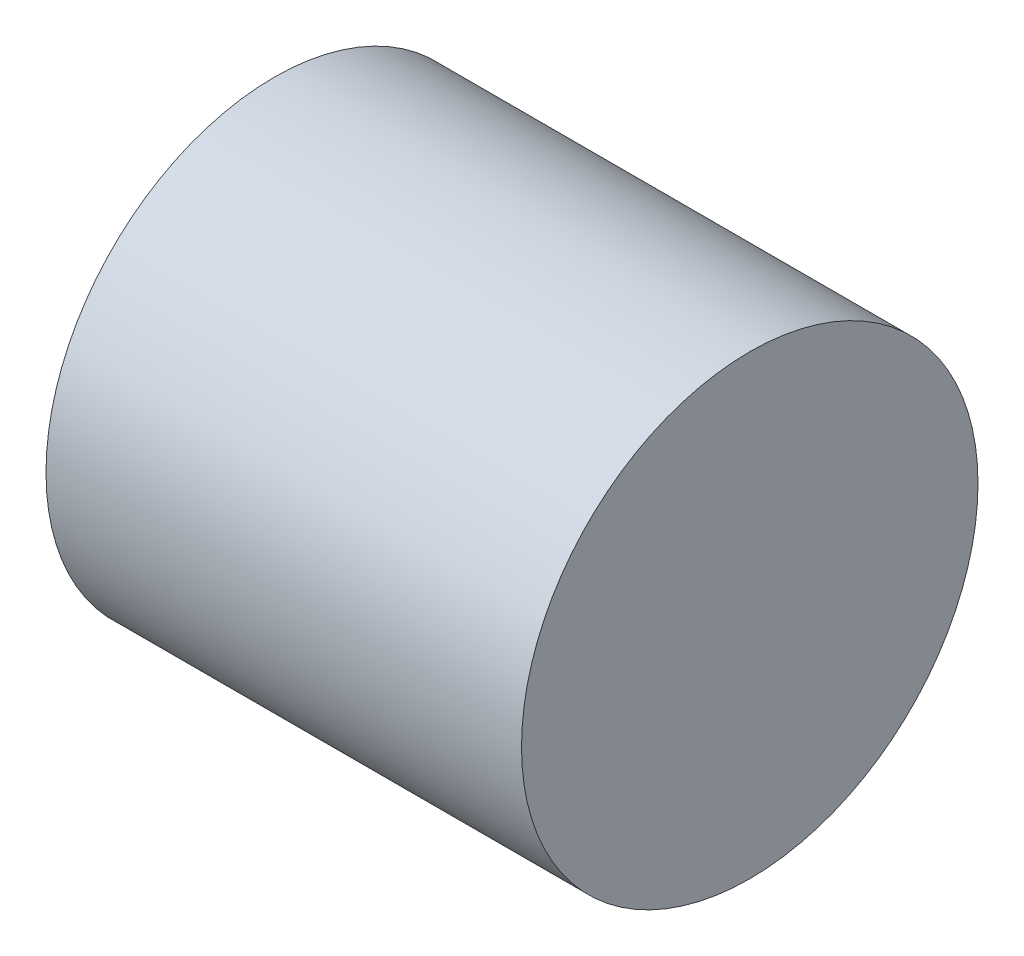
SolidWorks part; units mm, degrees
ref_plane "Front Plane" through (0, 0, 0) normal (0, 0, 1) x (1, 0, 0)
ref_plane "Top Plane" through (0, 0, 0) normal (0, 1, 0) x (1, 0, 0)
ref_plane "Right Plane" through (0, 0, 0) normal (1, 0, 0) x (0, 0, -1)
sketch "Sketch1" plane through (0, 0, 0) normal (0, 0, 1) x (1, 0, 0)
  line L0 (0, 0) -> (50, 0) construction
  line L1 (0, 0) -> (0, 12)
  line L2 (0, 12) -> (25, 12)
  line L3 (25, 12) -> (25, 0)
  line L4 (25, 0) -> (0, 0)
revolve "Revolve1" add sketch "Sketch1" angle 360 about L0
